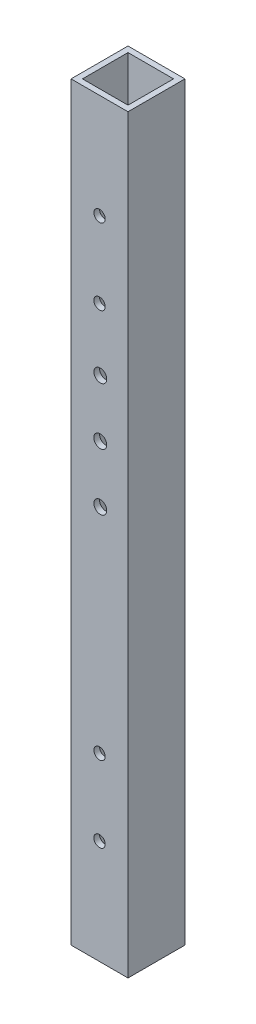
SolidWorks part; units mm, degrees
ref_plane "前视基准面" through (0, 0, 0) normal (0, 0, 1) x (1, 0, 0)
ref_plane "上视基准面" through (0, 0, 0) normal (0, 1, 0) x (1, 0, 0)
ref_plane "右视基准面" through (0, 0, 0) normal (1, 0, 0) x (0, 0, -1)
sketch "草图1" plane through (0, 0, 0) normal (0, 1, 0) x (1, 0, 0)
  line L0 (1.5, 1.5) -> (1.5, 13.5)
  line L1 (0, 0) -> (15, 0)
  line L2 (0, 0) -> (0, 15)
  line L3 (0, 15) -> (15, 15)
  line L4 (15, 0) -> (15, 15)
  line L5 (1.5, 13.5) -> (13.5, 13.5)
  line L6 (13.5, 1.5) -> (13.5, 13.5)
  line L7 (1.5, 1.5) -> (13.5, 1.5)
  dimension "D1" = 15
  dimension "D2" = 1.5
extrude "凸台-拉伸1" add sketch "草图1" along normal blind 197.65
sketch "草图2"
  line L0 (15, 197.65) -> (15, 0) construction
  line L2 (0, 197.65) -> (15, 197.65) construction
  circle A7 centre (7.5, 47.5) radius 1.5
  circle A8 centre (7.5, 27.5) radius 1.5
  circle A9 centre (7.7, 103.825) radius 1.7
  circle A10 centre (7.7, 118.825) radius 1.7
  circle A11 centre (7.7, 133.825) radius 1.7
  circle A12 centre (7.5, 150.15) radius 1.5
  circle A13 centre (7.5, 170.15) radius 1.5
other "对齐组1" parameters "D3"=3.4, "D4"=3, "D1"=0, "D2"=0, "D5"=7.3, "D6"=7.5, "D7"=27.5, "D8"=47.5, "D9"=63.825, "D10"=78.825, "D11"=93.825, "D12"=150.15, "D13"=170.15
other "对齐组2"
extrude "切除-拉伸1" cut sketch "草图2" against normal through all
